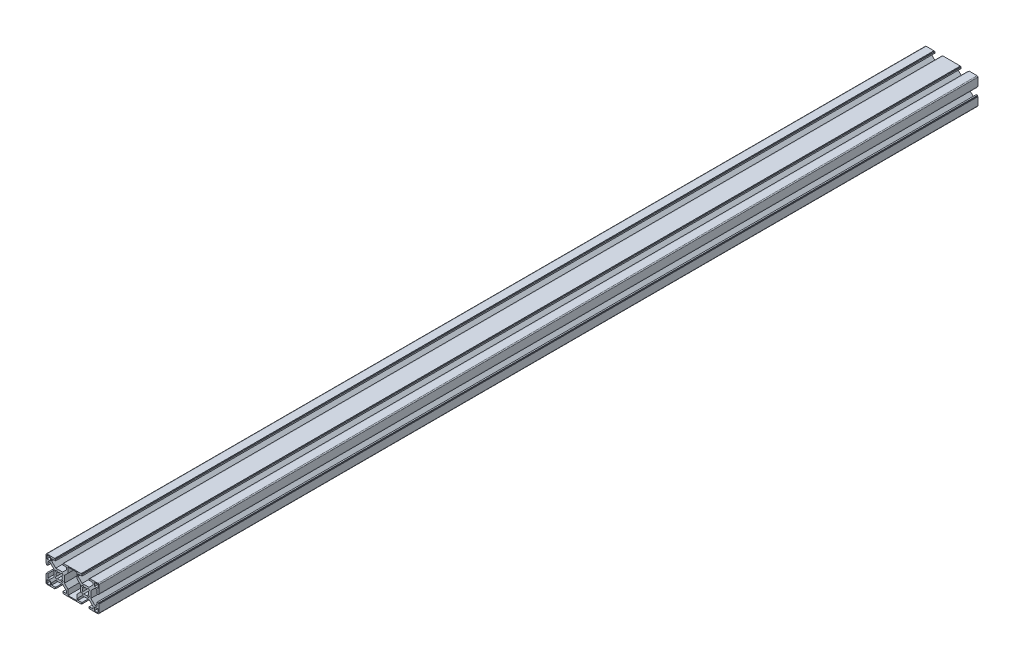
SolidWorks part; units mm, degrees
material "6063-O"
ref_plane "Plano frontal" through (0, 0, 0) normal (0, 0, 1) x (1, 0, 0)
ref_plane "Plano superior" through (0, 0, 0) normal (0, 1, 0) x (1, 0, 0)
ref_plane "Plano direito" through (0, 0, 0) normal (1, 0, 0) x (0, 0, -1)
sketch "Esboço1" plane through (0, 0, 0) normal (0, 0, 1) x (1, 0, 0)
  line L5 (0, 0) -> (-17.7944, 17.7944) construction
  line L6 (0, 3.5) -> (0, 6)
  line L8 (0, 6) -> (-3.8787, 6)
  line L9 (-3.5, 0) -> (-6, 0)
  line L48 (-6, 0) -> (-6, 3.8787)
  line L49 (-3.8787, 6) -> (-8.5, 10.6213)
  line L50 (-6, 3.8787) -> (-10.6213, 8.5)
  line L51 (0, 0) -> (-12.921, 0) construction
  line L52 (-8.5, 13) -> (-4.1, 13)
  line L53 (-4.1, 13) -> (-4.1, 14.5)
  line L54 (-4.1, 14.5) -> (-5.1, 14.5)
  line L55 (-5.1, 14.5) -> (-5.1, 15)
  line L56 (-5.1, 15) -> (-15, 15)
  line L57 (-15, 5.1) -> (-15, 15)
  line L58 (-14.5, 5.1) -> (-15, 5.1)
  line L59 (-14.5, 4.1) -> (-14.5, 5.1)
  line L60 (-13, 4.1) -> (-14.5, 4.1)
  line L61 (-13, 8.5) -> (-13, 4.1)
  line L62 (-1.6646, 3.0788) -> (-3.182, 4.5962)
  line L63 (-3.0788, 1.6646) -> (-4.5962, 3.182)
  line L64 (-4.5962, 3.182) -> (-3.182, 4.5962)
  line L65 (-8.5, 13) -> (-8.5, 10.6213)
  line L66 (-10, 14) -> (-14, 14)
  line L67 (-10, 14) -> (-10, 10)
  line L68 (-10, 10) -> (-14, 10)
  line L69 (-14, 14) -> (-14, 10)
  line L70 (-10, 14) -> (-14, 10) construction
  line L71 (-10, 10) -> (-14, 14) construction
  line L72 (-13, 8.5) -> (-10.6213, 8.5)
  circle A1 centre (0, 0) radius 3.5
  point P25 (-12, 12)
  dimension "D5" = 10.9
  dimension "D9" = 5.5
  dimension "D10" = 2
  dimension "D11" = 4
  dimension "D12" = 4
  dimension "D13" = 1
  dimension "D1" = 7
  dimension "D2" = 6
  dimension "D3" = 3
  dimension "D4" = 9.9
  dimension "D6" = 0.5
  dimension "D7" = 1.5
  dimension "D8" = 15
  dimension "D14" = 6.5
extrude "Ressalto-extrusão1" add sketch "Esboço1" along normal blind 1000 contours A1 L6 L8 L49 L65 L52 L53 L54 L55 L56 L57 L58 L59 L60 L61 L72 L50 L48 L9 L63 L64 L62 L69 L66 L67 L68
sketch "Esboço3" plane through (0, 0, 0) normal (1, 0, 0) x (0, 0, -1)
  line L0 (0, 0) -> (-1000, 0) construction
  dimension "D1" = 1000
pattern_circular "PadrãoCircular1" count 4 every 90 about axis through (0, 0, 0) along (0, 0, 1) of "Ressalto-extrusão1"
pattern_linear "Padrão linear1" count 2 spacing 30 along (1, 0, 0) of "Ressalto-extrusão1", "PadrãoCircular1"
sketch "Esboço4" plane through (0, 0, 0) normal (0, 0, -1) x (-1, 0, 0)
  line L0 (-20, 14) -> (-20, -14)
  line L1 (-20, -14) -> (-10, -14)
  line L2 (-10, -14) -> (-10, 14)
  line L3 (-10, 14) -> (-20, 14)
extrude "Corte-extrusão1" cut sketch "Esboço4" against normal through all
fillet "Filete1" radius 1 4 edges at (45, -15, 500) (45, 15, 500) (-15, 15, 500) (-15, -15, 500)
